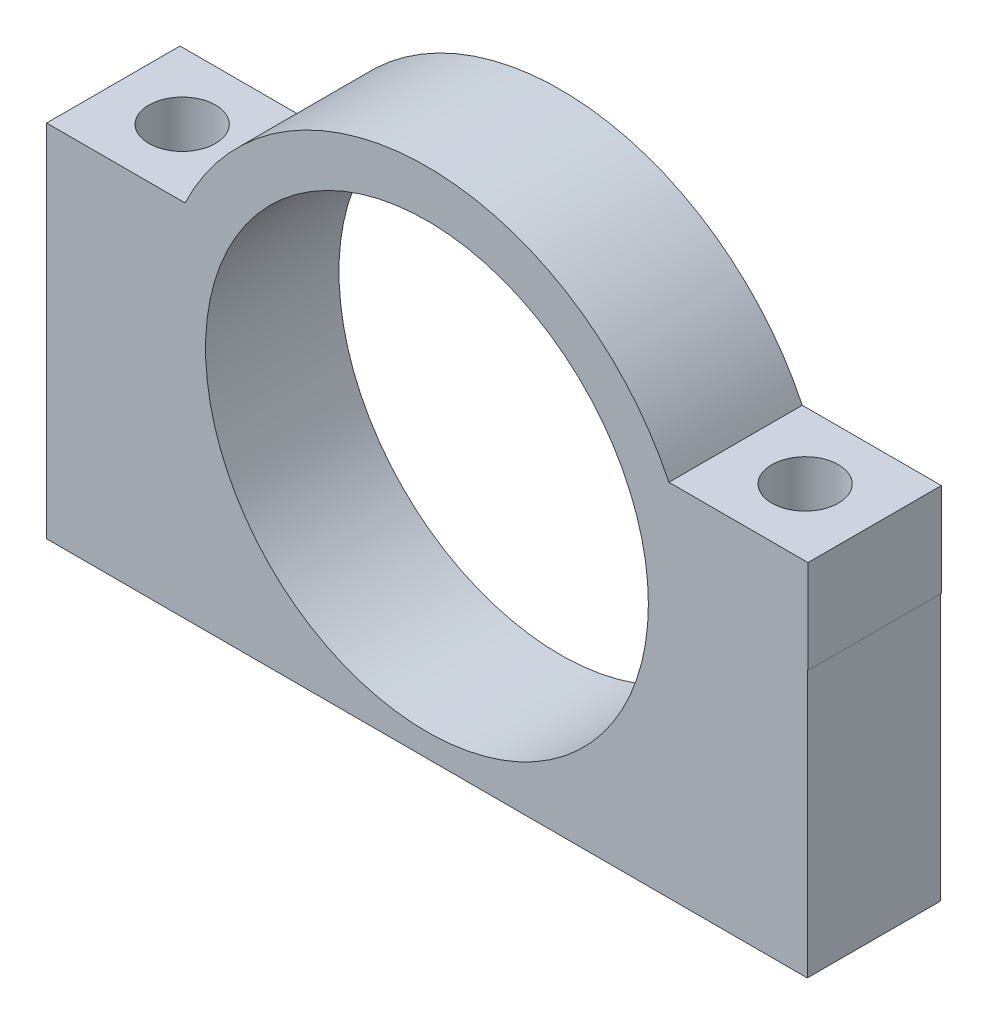
SolidWorks part; units mm, degrees
material "1060 Alloy"
ref_plane "Front Plane" through (0, 0, 0) normal (0, 0, 1) x (1, 0, 0)
ref_plane "Top Plane" through (0, 0, 0) normal (0, 1, 0) x (1, 0, 0)
ref_plane "Right Plane" through (0, 0, 0) normal (1, 0, 0) x (0, 0, -1)
sketch "Sketch1" plane through (0, 0, 0) normal (0, 0, 1) x (1, 0, 0)
  line L1 (36.2144, 2.1277) -> (36.2144, -23.2723)
  line L8 (-36.2144, 2.1277) -> (-36.2144, -23.2723)
  line L10 (36.2144, -23.2723) -> (-36.2144, -23.2723)
  line L20 (-20.9744, 2.1277) -> (-36.2144, 2.1277)
  line L21 (36.2144, 2.1277) -> (20.9744, 2.1277)
  arc A0 (-20.9744, 2.1277) -> (20.9744, 2.1277) centre (0, 0) ccw
  point P14 (-0.0005, -18.9639)
  dimension "D1" = 21.082
  dimension "D3" = 15.24
  dimension "D7" = 25.4
  dimension "D2" = 15.24
  dimension "D4" = 72.4287
  dimension "D5" = 25.4
extrude "Boss-Extrude1" add sketch "Sketch1" along normal blind 12.7
sketch "Sketch3" plane through (0, 0, 0) normal (0, 0, 1) x (1, 0, 0)
  line L0 (-20.9744, 2.1277) -> (-36.2144, 2.1277)
  line L1 (-36.2144, 2.1277) -> (-36.2144, 11.0177)
  line L2 (-36.2144, 11.0177) -> (-23.0366, 11.0177)
  line L3 (0, 0) -> (0, 19.1351) construction
  line L4 (36.2796, 2.1277) -> (36.2796, 11.0177)
  line L5 (36.2796, 11.0177) -> (23.0366, 11.0177)
  line L6 (20.9744, 2.1277) -> (36.2796, 2.1277)
  line L7 (45.4702, 0) -> (-43.7143, 0) construction
  line L8 (-20.9744, 2.1277) -> (-36.2144, 2.1277) construction
  line L9 (36.2144, 2.1277) -> (20.9744, 2.1277) construction
  line L10 (-36.2144, 2.1277) -> (-36.2144, -23.2723) construction
  line L11 (36.2796, -23.2723) -> (36.2796, 2.1277) construction
  arc A0 (20.9744, 2.1277) -> (-20.9744, 2.1277) centre (0, 0) ccw
  arc A2 (-23.0366, 11.0177) -> (23.0366, 11.0177) centre (0, 0) cw
  dimension "D3" = 8.89
  dimension "D1" = 21.082
  dimension "D2" = 13.1777
extrude "Boss-Extrude2" add sketch "Sketch3" along normal blind 12.7
sketch "Sketch18" plane through (0, 11.0177, 0) normal (0, 1, 0) x (1, 0, 0)
  line L0 (29.6581, -12.7) -> (29.6581, 0) construction
  line L1 (36.2796, -12.7) -> (23.0366, -12.7) construction
  line L2 (36.2796, 0) -> (23.0366, 0) construction
  line L3 (36.2796, -6.35) -> (23.0366, -6.35) construction
  line L4 (36.2796, -12.7) -> (36.2796, 0) construction
  line L5 (23.0366, -12.7) -> (23.0366, 0) construction
  line L7 (0, 0) -> (0, -12.7) construction
  line L8 (-23.0366, -12.7) -> (23.0366, -12.7) construction
  line L9 (-36.2796, -6.35) -> (-23.0366, -6.35) construction
  line L10 (-29.6581, -12.7) -> (-29.6581, 0) construction
  circle A0 centre (-29.6581, -6.35) radius 3.175
  circle A1 centre (29.6581, -6.35) radius 3.175
  circle A2 centre (29.6581, -6.35) radius 3.8349
  circle A3 centre (-29.6581, -6.35) radius 3.8349
  dimension "D1" = 6.35
  dimension "D2" = 7.6699
extrude "Cut-Extrude1" cut sketch "Sketch18" against normal up to surface (34.29 mm away) contours A0 | A1 up to face at (0, -23.2723, 6.35)
